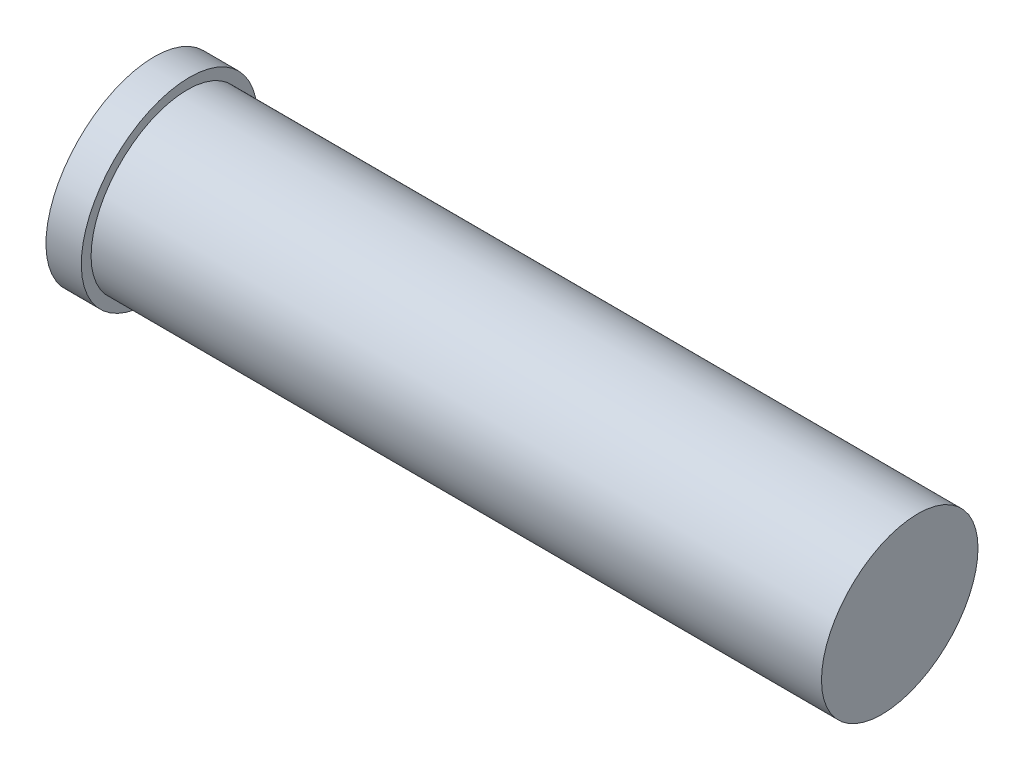
SolidWorks part; units mm, degrees
material "Caucho"
ref_plane "Alzado" through (0, 0, 0) normal (0, 0, 1) x (1, 0, 0)
ref_plane "Planta" through (0, 0, 0) normal (0, 1, 0) x (1, 0, 0)
ref_plane "Vista lateral" through (0, 0, 0) normal (1, 0, 0) x (0, 0, -1)
sketch3d "Sk_Puno"
  line L0 (250.774, 39.9286, -26.4554) -> (379.4801, 26.798, -39.196)
  dimension "D1" = 130
sweep "Puno" add path "Sk_Puno" circular profile diameter 32 parameters "D3"=32
sketch3d "Sk_Collarin"
  line L0 (250.774, 39.9286, -26.4554) -> (256.7143, 39.3226, -27.0434)
  dimension "D1" = 6
sweep "Collarin" add path "Sk_Collarin" circular profile diameter 36 parameters "D3"=36
sketch3d "Sk_Agujero_puno"
  line L0 (249.7839, 40.0296, -26.3574) -> (377.5, 27, -39)
  dimension "D1" = 129
sweep "Agujero_puno" cut path "Sk_Agujero_puno" circular profile diameter 22.2 parameters "D3"=22.2
